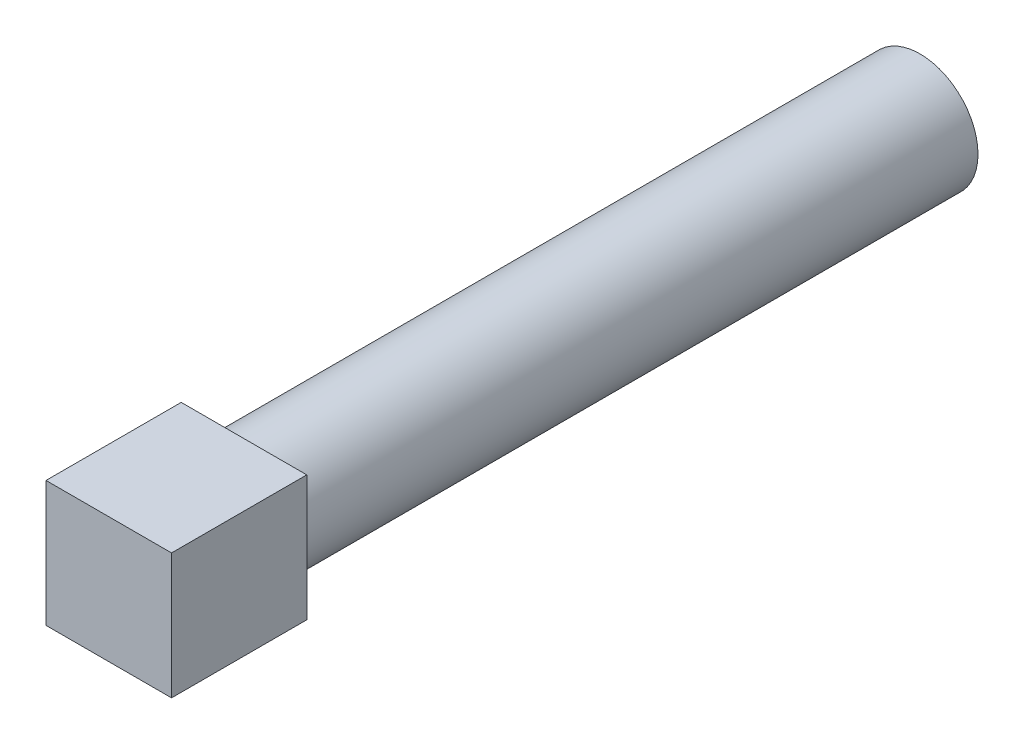
SolidWorks part; units mm, degrees
ref_plane "Front Plane" through (0, 0, 0) normal (0, 0, 1) x (1, 0, 0)
ref_plane "Top Plane" through (0, 0, 0) normal (0, 1, 0) x (1, 0, 0)
ref_plane "Right Plane" through (0, 0, 0) normal (1, 0, 0) x (0, 0, -1)
sketch "Sketch1" plane through (0, 0, 0) normal (0, 0, 1) x (1, 0, 0)
  circle A0 centre (0, 0) radius 6
  dimension "D1" = 12
extrude "Boss-Extrude1" add sketch "Sketch1" along normal blind 70
ref_plane "Plane1" through (0, 0, 84) normal (0, 0, 1) x (1, 0, 0)
sketch "Sketch2" plane through (0, 0, 84) normal (0, 0, 1) x (1, 0, 0)
  line L1 (-6.5, 6.5) -> (6.5, 6.5)
  line L2 (-6.5, 6.5) -> (-6.5, -6.5)
  line L3 (-6.5, -6.5) -> (6.5, -6.5)
  line L4 (6.5, 6.5) -> (6.5, -6.5)
  line L5 (-6.5, 6.5) -> (6.5, -6.5) construction
  line L6 (-6.5, -6.5) -> (6.5, 6.5) construction
  point P0 (0, 0)
  dimension "D1" = 13
  dimension "D2" = 13
  dimension "D3" = 13
extrude "Boss-Extrude2" add sketch "Sketch2" against normal up to surface (14 mm away) up to face at (6, 0, 70)
